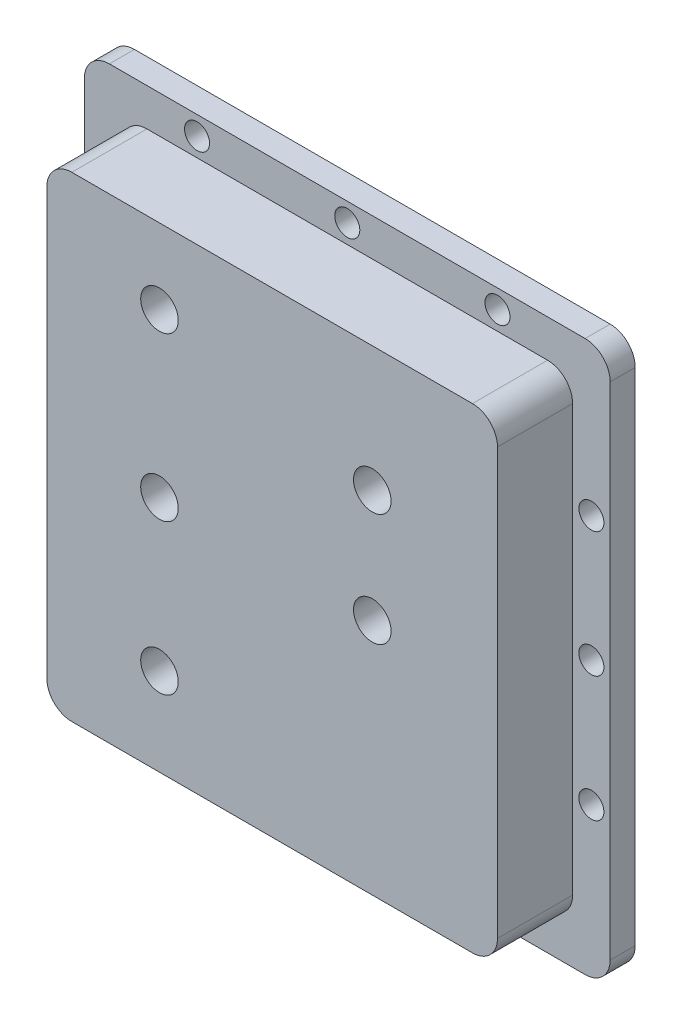
SolidWorks part; units mm, degrees
ref_plane "前视基准面" through (0, 0, 0) normal (0, 0, 1) x (1, 0, 0)
ref_plane "上视基准面" through (0, 0, 0) normal (0, 1, 0) x (1, 0, 0)
ref_plane "右视基准面" through (0, 0, 0) normal (1, 0, 0) x (0, 0, -1)
sketch "草图1" plane through (0, 0, 0) normal (0, 0, 1) x (1, 0, 0)
  line L1 (-80, -95) -> (80, -95)
  line L2 (-90, -85) -> (-90, 85)
  line L3 (-80, 95) -> (80, 95)
  line L4 (90, -85) -> (90, 85)
  line L5 (-90, -95) -> (90, 95) construction
  line L6 (-90, 95) -> (90, -95) construction
  arc A0 (-80, -95) -> (-90, -85) centre (-80, -85) cw
  arc A1 (80, -95) -> (90, -85) centre (80, -85) ccw
  arc A2 (80, 95) -> (90, 85) centre (80, 85) cw
  arc A3 (-90, 85) -> (-80, 95) centre (-80, 85) cw
  point P0 (0, 0)
  dimension "D3" = 10
  dimension "D1" = 190
  dimension "D2" = 180
extrude "凸台-拉伸1" add sketch "草图1" along normal blind 30
sketch "草图2" plane through (0, 0, 0) normal (0, 0, -1) x (-1, 0, 0)
  line L0 (0, 0) -> (0, 102.5) construction
  line L1 (-95, -110) -> (95, -110)
  line L2 (-105, -100) -> (-105, 100)
  line L3 (-95, 110) -> (95, 110)
  line L4 (105, -100) -> (105, 100)
  line L5 (-105, -110) -> (105, 110) construction
  line L6 (-105, 110) -> (105, -110) construction
  line L7 (-97.5, -102.5) -> (97.5, -102.5) construction
  line L8 (-97.5, -102.5) -> (-97.5, 102.5) construction
  line L9 (-97.5, 102.5) -> (97.5, 102.5) construction
  line L10 (97.5, -102.5) -> (97.5, 102.5) construction
  line L11 (-97.5, -102.5) -> (97.5, 102.5) construction
  line L12 (-97.5, 102.5) -> (97.5, -102.5) construction
  line L13 (0, 0) -> (97.5, 0) construction
  arc A0 (95, 110) -> (105, 100) centre (95, 100) cw
  arc A1 (95, -110) -> (105, -100) centre (95, -100) ccw
  arc A2 (-95, -110) -> (-105, -100) centre (-95, -100) cw
  arc A3 (-105, 100) -> (-95, 110) centre (-95, 100) cw
  circle A4 centre (97.5, 0) radius 5
  circle A5 centre (0, 102.5) radius 5
  circle A6 centre (60, 102.5) radius 5
  circle A7 centre (97.5, 50) radius 5
  circle A8 centre (97.5, -50) radius 5
  circle A9 centre (60, -102.5) radius 5
  circle A10 centre (0, -102.5) radius 5
  circle A11 centre (-60, 102.5) radius 5
  circle A12 centre (-60, -102.5) radius 5
  circle A13 centre (-97.5, -50) radius 5
  circle A14 centre (-97.5, 0) radius 5
  circle A15 centre (-97.5, 50) radius 5
  point P0 (0, 0)
  point P18 (0, 0)
  dimension "D3" = 10
  dimension "D6" = 10
  dimension "D7" = 10
  dimension "D8" = 10
  dimension "D9" = 60
  dimension "D10" = 10
  dimension "D11" = 50
  dimension "D1" = 220
  dimension "D2" = 210
  dimension "D4" = 205
  dimension "D5" = 195
extrude "凸台-拉伸2" add sketch "草图2" along normal blind 10
sketch "草图3" plane through (0, 0, -10) normal (0, 0, -1) x (-1, 0, 0)
  line L1 (-70, -80) -> (70, -80)
  line L2 (-70, -80) -> (-70, 80)
  line L3 (-70, 80) -> (70, 80)
  line L4 (70, -80) -> (70, 80)
  line L5 (-70, -80) -> (70, 80) construction
  line L6 (-70, 80) -> (70, -80) construction
  point P0 (0, 0)
  dimension "D1" = 160
  dimension "D2" = 140
extrude "切除-拉伸1" cut sketch "草图3" against normal offset from surface (10 mm away) 30 up to face at (0, 0, 30)
sketch "草图4" plane through (0, 0, 30) normal (0, 0, 1) x (1, 0, 0)
  line L0 (0, 0) -> (-45, 0) construction
  line L1 (-45, -60) -> (-45, 65) construction
  line L2 (40, 45) -> (40, 0) construction
  circle A0 centre (40, 45) radius 7.5
  circle A1 centre (40, 0) radius 7.5
  circle A2 centre (-45, 0) radius 7.5
  circle A3 centre (-45, 65) radius 7.5
  circle A4 centre (-45, -60) radius 7.5
  dimension "D1" = 15
  dimension "D2" = 15
  dimension "D3" = 15
  dimension "D4" = 15
  dimension "D5" = 15
  dimension "D6" = 65
  dimension "D7" = 60
  dimension "D9" = 45
  dimension "D10" = 40
  dimension "D8" = 45
extrude "切除-拉伸2" cut sketch "草图4" against normal through all both and the other way through all
